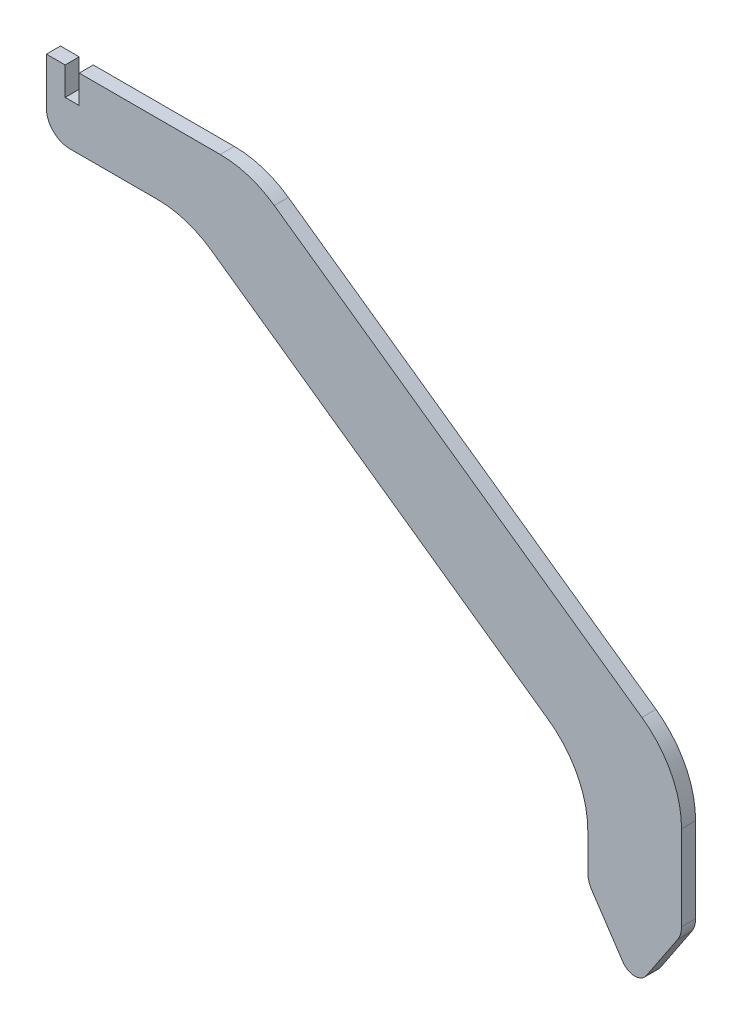
SolidWorks part; units mm, degrees
material "PBT General Purpose"
ref_plane "Front Plane" through (0, 0, 0) normal (0, 0, 1) x (1, 0, 0)
ref_plane "Top Plane" through (0, 0, 0) normal (0, 1, 0) x (1, 0, 0)
ref_plane "Right Plane" through (0, 0, 0) normal (1, 0, 0) x (0, 0, -1)
sketch "Sketch1" plane through (0, 0, 0) normal (0, 0, 1) x (1, 0, 0)
  line L13 (0, 0) -> (0.4, 0)
  line L14 (4.3431, 0) -> (13.55, -6.5)
  line L15 (13.55, -6.5) -> (13.55, -9.5)
  line L16 (13.55, -9.5) -> (12.55, -11)
  line L17 (12.55, -11) -> (11.55, -9.5)
  line L18 (11.55, -9.5) -> (11.55, -7.5362)
  line L19 (11.55, -7.5362) -> (3, -1.5)
  line L20 (3, -1.5) -> (0, -1.5)
  line L21 (0, -1.5) -> (0, 0)
  line L22 (0.4, 0) -> (0.4, -0.6)
  line L23 (0.4, -0.6) -> (0.7, -0.6)
  line L24 (0.7, -0.6) -> (0.7, 0)
  line L25 (0.7, 0) -> (4.3431, 0)
  line L26 (13.55, -9.5) -> (11.55, -9.5) construction
  point P13 (0.55, -0.6)
  point P16 (12.55, -9.5)
  dimension "D1" = 0.3
  dimension "D3" = 1.5
  dimension "D4" = 0.4
  dimension "D5" = 12
  dimension "D6" = 11
  dimension "D7" = 2
  dimension "D8" = 2
  dimension "D2" = 0.6
  dimension "D9" = 3
  dimension "D10" = 3
  dimension "D11" = 1.5
extrude "Boss-Extrude1" add sketch "Sketch1" along normal mid plane 0.3
fillet "Fillet1" radius 0.3 1 edges at (12.55, -11, 0)
fillet "Fillet2" radius 0.5 3 edges at (0, -1.5, 0) (13.55, -9.5, 0) (11.55, -9.5, 0)
fillet "Fillet3" radius 2 4 edges at (4.3431, 0, 0) (13.55, -6.5, 0) (11.55, -7.5362, 0) (3, -1.5, 0)
equation "\"t\"= 0.3'thickness of the sheets"
equation "\"FlexJoint\"= 0.15'Width of flextures"
equation "\"FoldJoint\"= 0.4'Width of folding joints"
equation "\"AssembleAngle\"= 90'Angle of assembly parts"
equation "\"D1@Boss-Extrude1\"=\"t\""
equation "\"D1@Sketch1\"=\"t\""
